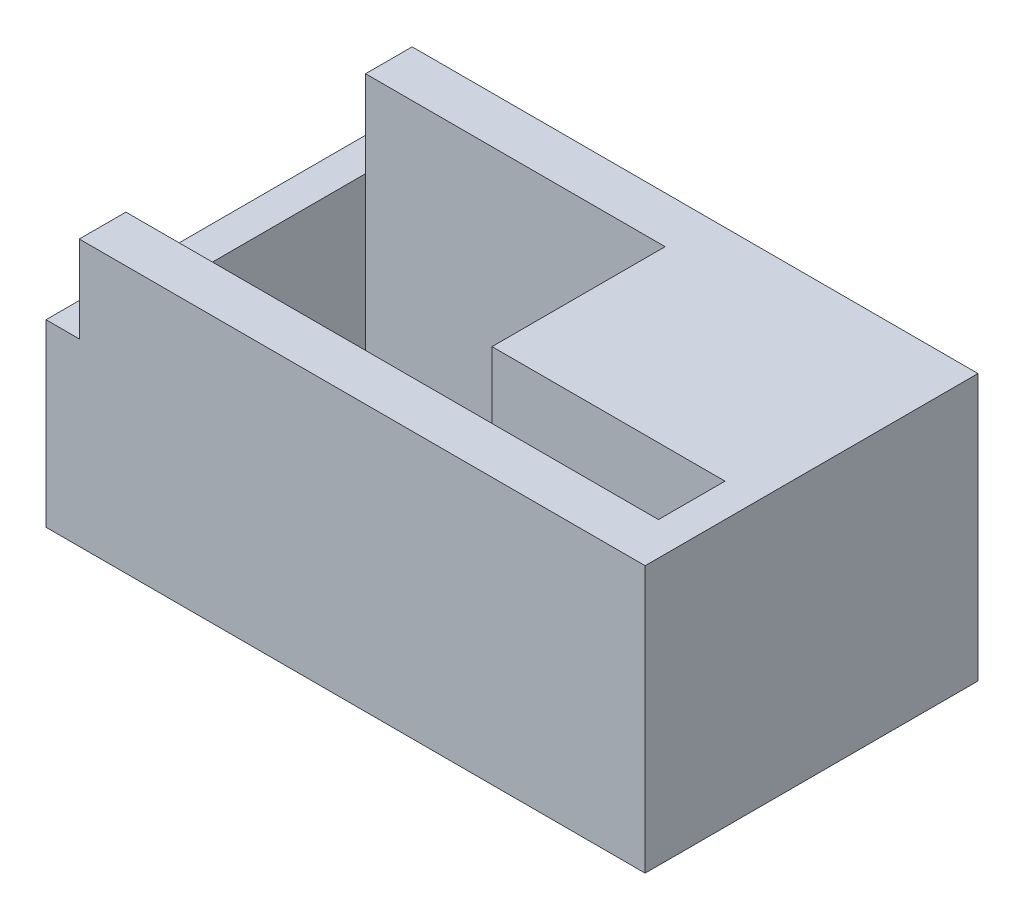
SolidWorks part; units mm, degrees
ref_plane "前视基准面" through (0, 0, 0) normal (0, 0, 1) x (1, 0, 0)
ref_plane "上视基准面" through (0, 0, 0) normal (0, 1, 0) x (1, 0, 0)
ref_plane "右视基准面" through (0, 0, 0) normal (1, 0, 0) x (0, 0, -1)
sketch "草图1" plane through (0, 0, 0) normal (1, 0, 0) x (0, 0, -1)
  line L1 (0, 0) -> (-50, 0)
  line L2 (0, 0) -> (0, 40)
  line L3 (0, 40) -> (-50, 40)
  line L4 (-50, 0) -> (-50, 40)
  dimension "D1" = 40
  dimension "D2" = 50
extrude "凸台-拉伸1" add sketch "草图1" along normal blind 85
sketch "草图2" plane through (0, 40, 0) normal (0, 1, 0) x (1, 0, 0)
  line L0 (0, 0) -> (0, -50) construction
  line L1 (45, -7) -> (0, -7)
  line L2 (45, -7) -> (45, -33)
  line L4 (0, -7) -> (0, -35)
  line L5 (85, 0) -> (0, 0) construction
  line L6 (80, -43) -> (0, -43)
  line L7 (80, -43) -> (80, -33)
  line L8 (80, -33) -> (45, -33)
  line L9 (0, -43) -> (0, -35)
  line L11 (85, -50) -> (0, -50) construction
  dimension "D1" = 7
  dimension "D2" = 7
  dimension "D3" = 80
  dimension "D4" = 45
  dimension "D5" = 10
extrude "切除-拉伸1" cut sketch "草图2" against normal blind 60
sketch "草图3" plane through (0, 0, 0) normal (0, -1, 0) x (1, 0, 0)
  line L0 (0, 43) -> (80, 43) construction
  line L1 (0, 43) -> (45, 43)
  line L2 (0, 43) -> (0, 28)
  line L3 (0, 28) -> (45, 28)
  line L4 (45, 33) -> (45, 28)
  line L5 (40.0398, 43) -> (-101.703, 43) construction
  line L7 (45, 43) -> (80, 43)
  line L9 (45, 33) -> (80, 33)
  line L10 (80, 43) -> (80, 33)
  dimension "D1" = 35
  dimension "D2" = 15
extrude "凸台-拉伸2" add sketch "草图3" against normal blind 25
sketch "草图4" plane through (0, 0, 0) normal (-1, 0, 0) x (0, 0, 1)
  line L1 (50, 0) -> (0, 0)
  line L2 (50, 0) -> (50, 27)
  line L3 (50, 27) -> (0, 27)
  line L4 (0, 0) -> (0, 27)
  dimension "D1" = 27
extrude "凸台-拉伸3" add sketch "草图4" along normal blind 5
